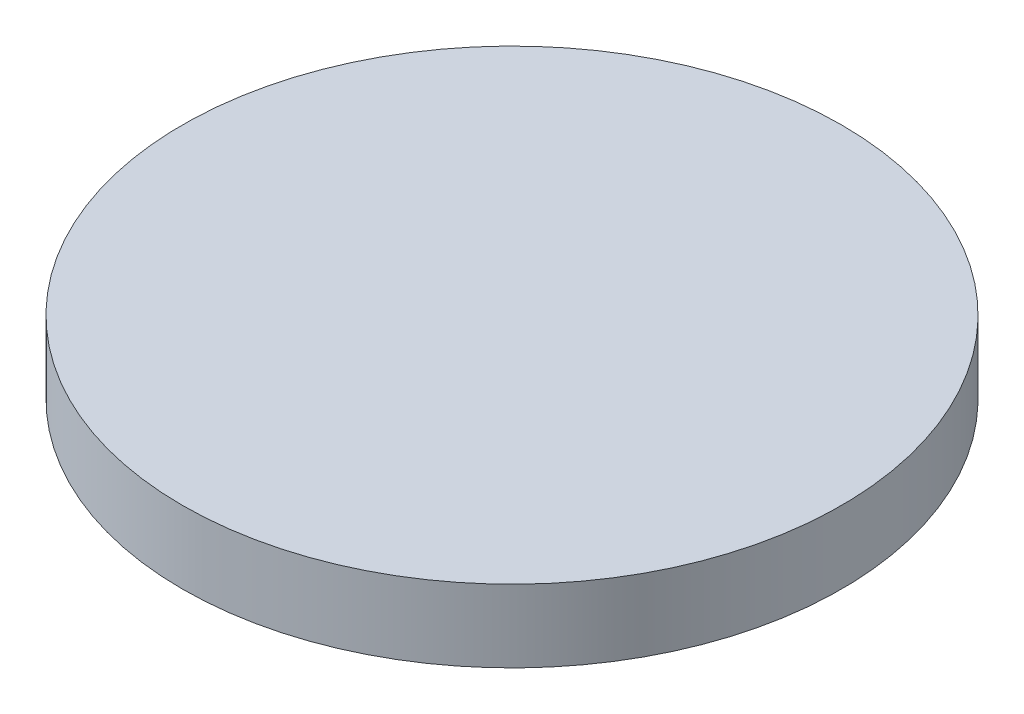
SolidWorks part; units mm, degrees
ref_plane "Front Plane" through (0, 0, 0) normal (0, 0, 1) x (1, 0, 0)
ref_plane "Top Plane" through (0, 0, 0) normal (0, 1, 0) x (1, 0, 0)
ref_plane "Right Plane" through (0, 0, 0) normal (1, 0, 0) x (0, 0, -1)
sketch "Sketch1" plane through (0, 0, 0) normal (0, 1, 0) x (1, 0, 0)
  circle A0 centre (0, 0) radius 25
  dimension "D1" = 50
extrude "Boss-Extrude1" add sketch "Sketch1" along normal blind 5.5 contours A0
sketch "Sketch2" plane through (0, 0, 0) normal (0, -1, 0) x (1, 0, 0)
  circle A0 centre (0, 0) radius 24
  dimension "D1" = 48
extrude "Cut-Extrude1" cut sketch "Sketch2" against normal offset from surface (3.5 mm away) 2 up to face at (0, 5.5, 25)
sketch "Sketch3" plane through (0, 3.5, 0) normal (0, -1, 0) x (-1, 0, 0)
  circle A0 centre (0, 0) radius 19.9
  circle A1 centre (0, 0) radius 20.4
  dimension "D1" = 39.8
  dimension "D2" = 40.8
extrude "Cut-Extrude2" cut sketch "Sketch3" against normal offset from surface (1 mm away) 1 up to face at (0, 5.5, 25)
